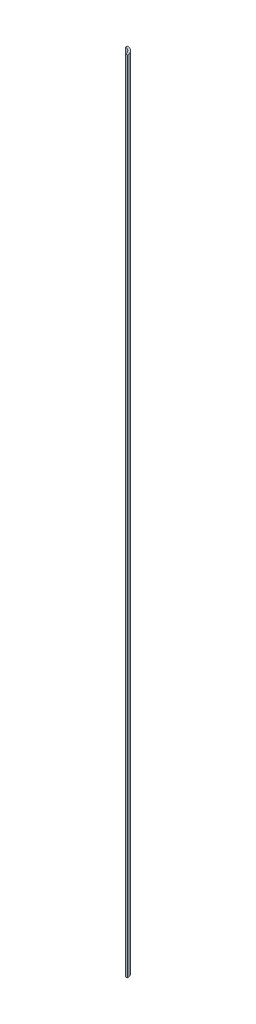
SolidWorks part; units mm, degrees
material "6061 Alloy"
ref_plane "Front Plane" through (0, 0, 0) normal (0, 0, 1) x (1, 0, 0)
ref_plane "Top Plane" through (0, 0, 0) normal (0, 1, 0) x (1, 0, 0)
ref_plane "Right Plane" through (0, 0, 0) normal (1, 0, 0) x (0, 0, -1)
sketch "Sketch1" plane through (0, 0, 0) normal (0, 1, 0) x (1, 0, 0)
  line L0 (0, 2) -> (0, 1.5)
  line L1 (1.5, 0) -> (2, 0)
  arc A0 (2, 0) -> (0, 2) centre (0, 0) ccw
  arc A1 (1.5, 0) -> (0, 1.5) centre (0, 0) ccw
  dimension "D1" = 4
  dimension "D2" = 3
extrude "Boss-Extrude1" add sketch "Sketch1" along normal blind 203
